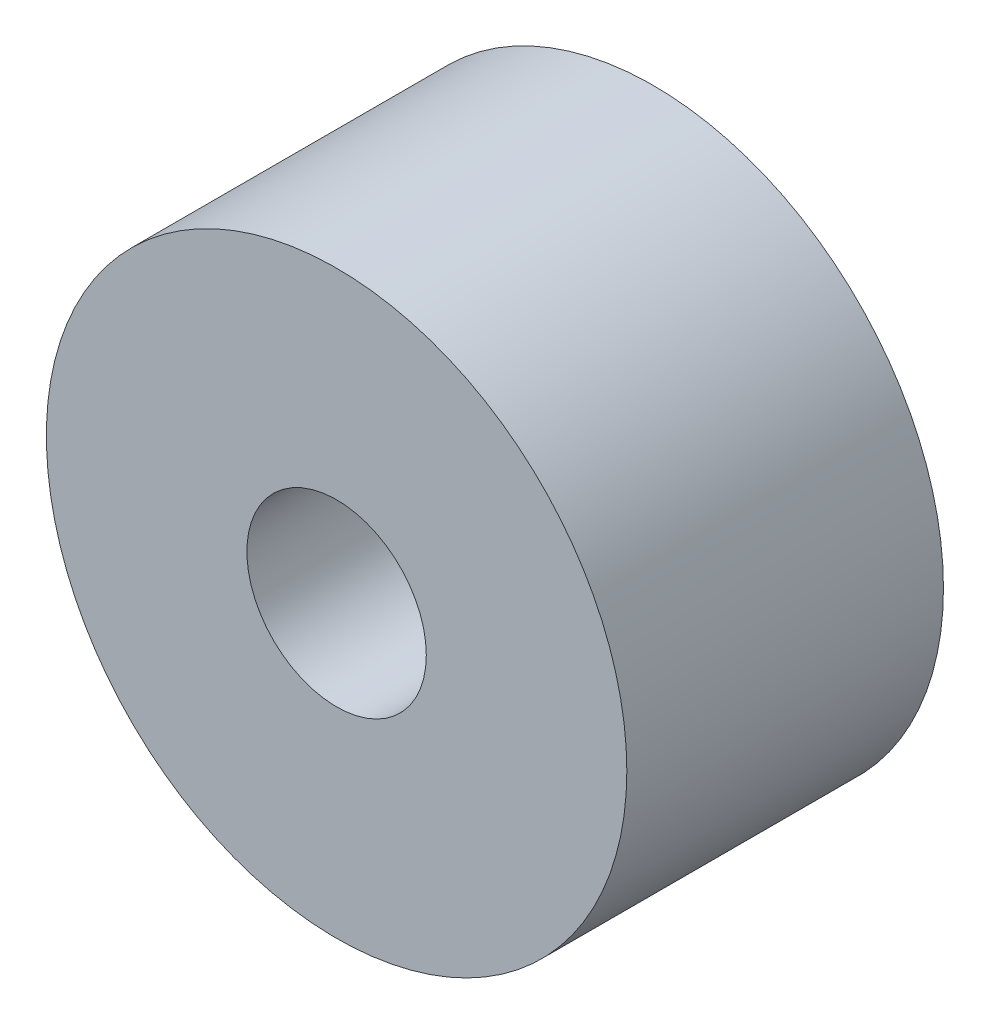
SolidWorks part; units mm, degrees
ref_plane "Front Plane" through (0, 0, 0) normal (0, 0, 1) x (1, 0, 0)
ref_plane "Top Plane" through (0, 0, 0) normal (0, 1, 0) x (1, 0, 0)
ref_plane "Right Plane" through (0, 0, 0) normal (1, 0, 0) x (0, 0, -1)
sketch "Sketch1" plane through (0, 0, 0) normal (0, 0, 1) x (1, 0, 0)
  circle A0 centre (0, 0) radius 5.5
  dimension "D1" = 11
extrude "Boss-Extrude1" add sketch "Sketch1" along normal blind 6
hole_wizard "M3 Clearance Hole1" positions "Sketch2" profile "Sketch3" hole size "M3" standard "ANSI Metric" end condition through all
sketch "Sketch2" plane through (0, 0, 6) normal (0, 0, 1) x (1, 0, 0)
  point P0 (0, 0)
sketch "Sketch3" plane through (0, 0, 6) normal (1, 0, 0) x (0, -1, 0)
  line L0 (0, 0) -> (0, 6)
  line L1 (0, 6) -> (1.7, 6)
  line L2 (1.7, 6) -> (1.7, 0)
  line L5 (1.7, 0) -> (0, 0)
  line L11 (0, -6.35) -> (0, 107.95) construction
  dimension "Thru Hole Dia." = 3.4
  dimension "Thru Hole Depth" = 6
